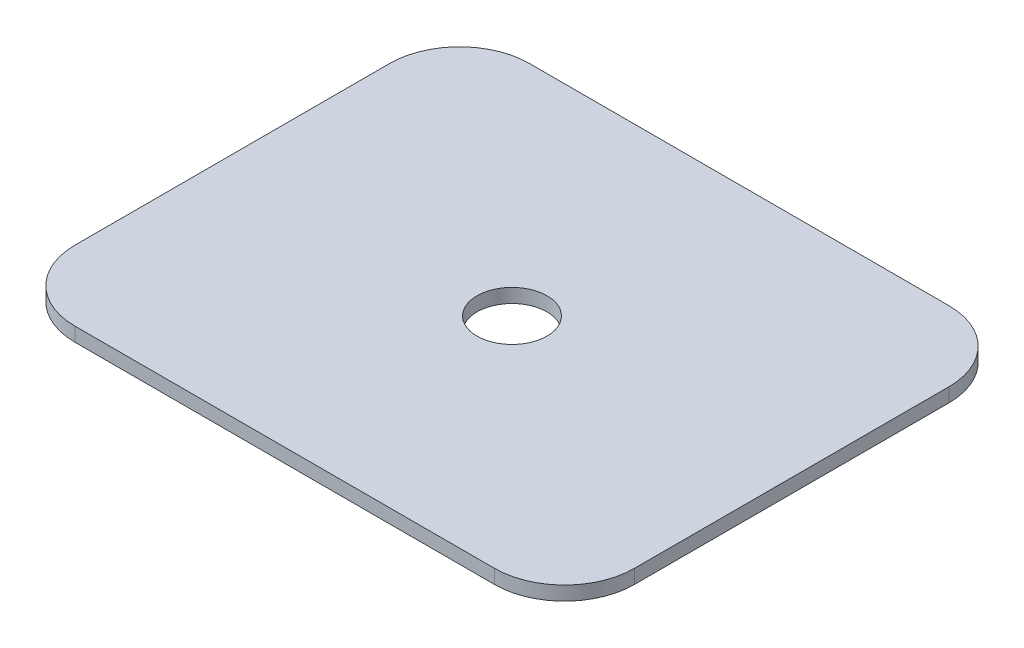
SolidWorks part; units mm, degrees
ref_plane "Спереди" through (0, 0, 0) normal (0, 0, 1) x (1, 0, 0)
ref_plane "Сверху" through (0, 0, 0) normal (0, 1, 0) x (1, 0, 0)
ref_plane "Справа" through (0, 0, 0) normal (1, 0, 0) x (0, 0, -1)
sketch "Эскиз10" plane through (0, 0, 0) normal (0, 1, 0) x (1, 0, 0)
  line L1 (-30, 2) -> (30, 2)
  line L2 (-40, -8) -> (-40, -53)
  line L3 (-30, -63) -> (30, -63)
  line L4 (40, -8) -> (40, -53)
  line L5 (-40, 2) -> (40, -63) construction
  line L6 (-40, -63) -> (40, 2) construction
  arc A0 (-30, 2) -> (-40, -8) centre (-30, -8) ccw
  arc A1 (40, -8) -> (30, 2) centre (30, -8) ccw
  arc A2 (30, -63) -> (40, -53) centre (30, -53) ccw
  arc A3 (-40, -53) -> (-30, -63) centre (-30, -53) ccw
  circle A4 centre (0, -30.5) radius 5
  point P0 (0, -30.5)
  dimension "D1" = 10
extrude "Вытянуть1" add sketch "Эскиз10" along normal blind 2
